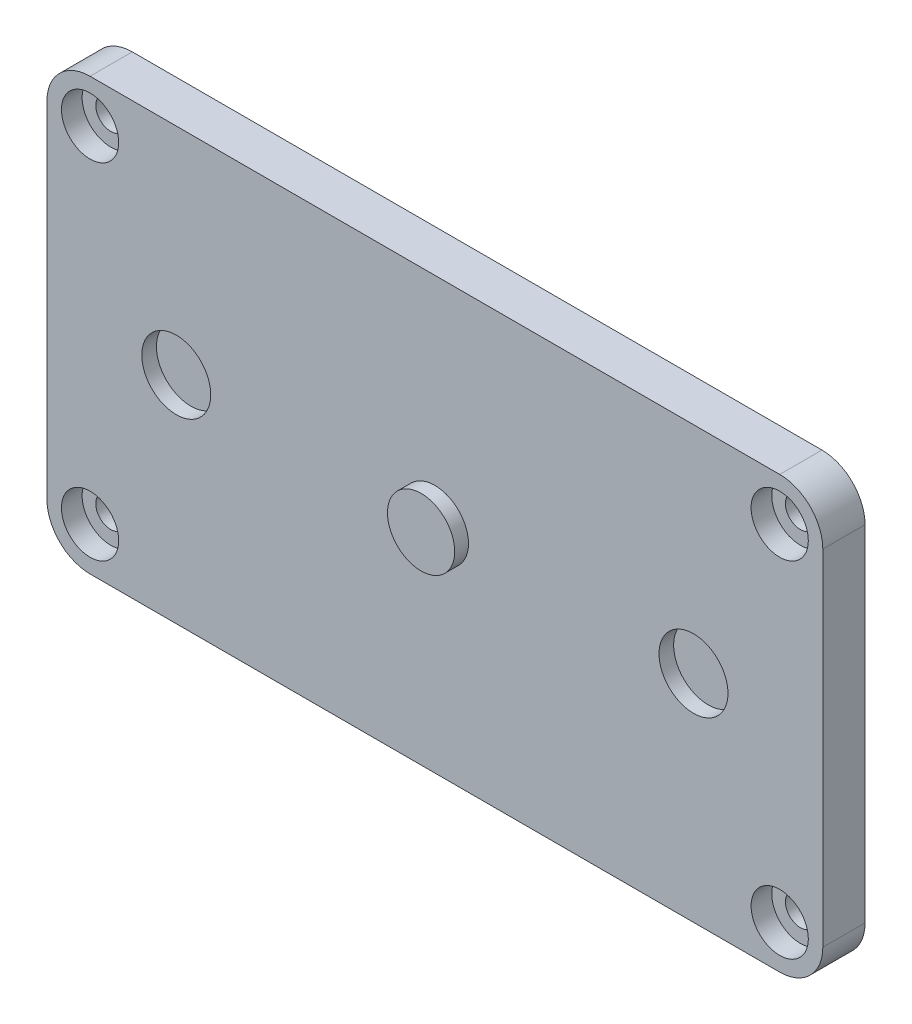
SolidWorks part; units mm, degrees
material "ABS"
ref_plane "Front Plane" through (0, 0, 0) normal (0, 0, 1) x (1, 0, 0)
ref_plane "Top Plane" through (0, 0, 0) normal (0, 1, 0) x (1, 0, 0)
ref_plane "Right Plane" through (0, 0, 0) normal (1, 0, 0) x (0, 0, -1)
sketch "Sketch1" plane through (0, 0, 0) normal (0, 0, 1) x (1, 0, 0)
  line L1 (-50.8, -31.75) -> (50.8, -31.75)
  line L2 (-57.15, -25.4) -> (-57.15, 25.4)
  line L3 (-50.8, 31.75) -> (50.8, 31.75)
  line L4 (57.15, -25.4) -> (57.15, 25.4)
  line L5 (-57.15, -31.75) -> (57.15, 31.75) construction
  line L6 (-57.15, 31.75) -> (57.15, -31.75) construction
  arc A0 (50.8, -31.75) -> (57.15, -25.4) centre (50.8, -25.4) ccw
  arc A1 (50.8, 31.75) -> (57.15, 25.4) centre (50.8, 25.4) cw
  arc A2 (-57.15, 25.4) -> (-50.8, 31.75) centre (-50.8, 25.4) cw
  arc A3 (-50.8, -31.75) -> (-57.15, -25.4) centre (-50.8, -25.4) cw
  circle A4 centre (-50.8, -25.4) radius 2.2098
  circle A5 centre (-50.8, 25.4) radius 2.2098
  circle A6 centre (50.8, 25.4) radius 2.2098
  circle A7 centre (50.8, -25.4) radius 2.2098
  point P0 (0, 0)
  dimension "D3" = 6.35
  dimension "D4" = 4.4196
  dimension "D1" = 114.3
  dimension "D2" = 63.5
extrude "Boss-Extrude1" add sketch "Sketch1" along normal blind 6.223
sketch "Sketch2" plane through (0, 0, 6.223) normal (0, 0, 1) x (1, 0, 0)
  circle A0 centre (-50.8, 25.4) radius 4.2164
  circle A1 centre (50.8, 25.4) radius 4.2164
  circle A2 centre (50.8, -25.4) radius 4.2164
  circle A3 centre (-50.8, -25.4) radius 4.2164
  dimension "D1" = 8.4328
extrude "Cut-Extrude1" cut sketch "Sketch2" against normal blind 3.048
sketch "Sketch3" plane through (0, 0, 6.223) normal (0, 0, 1) x (1, 0, 0)
  circle A0 centre (0, 0) radius 5.08 construction
  circle A1 centre (38.1, 0) radius 5.08
  circle A2 centre (-38.1, 0) radius 5.08
  dimension "D3" = 10.16
  dimension "D1" = 38.1
  dimension "D2" = 38.1
extrude "Cut-Extrude2" cut sketch "Sketch3" against normal blind 2.159
sketch "Sketch4" plane through (0, 0, 6.223) normal (0, 0, 1) x (1, 0, 0)
  circle A0 centre (0, 0) radius 4.953
  dimension "D1" = 9.906
extrude "Boss-Extrude2" add sketch "Sketch4" along normal blind 2.032
equation "\"tolerance\"= 0.005"
equation "\"D1@Boss-Extrude1\"= .115 + .125 + \"tolerance\""
equation "\"D4@Sketch1\" = .164 + \"tolerance\" * 2"
equation "\"D1@Sketch2\"= .322 + \"tolerance\" * 2"
equation "\"D1@Cut-Extrude1\"= .115 + \"tolerance\""
equation "\"D3@Sketch3\"= .39 + \"tolerance\" * 2"
equation "\"D1@Cut-Extrude2\"= .08 + \"tolerance\""
equation "\"D1@Sketch4\"=.4-\"tolerance\"*2"
equation "\"D1@Boss-Extrude2\"=.085in-\"tolerance\""
